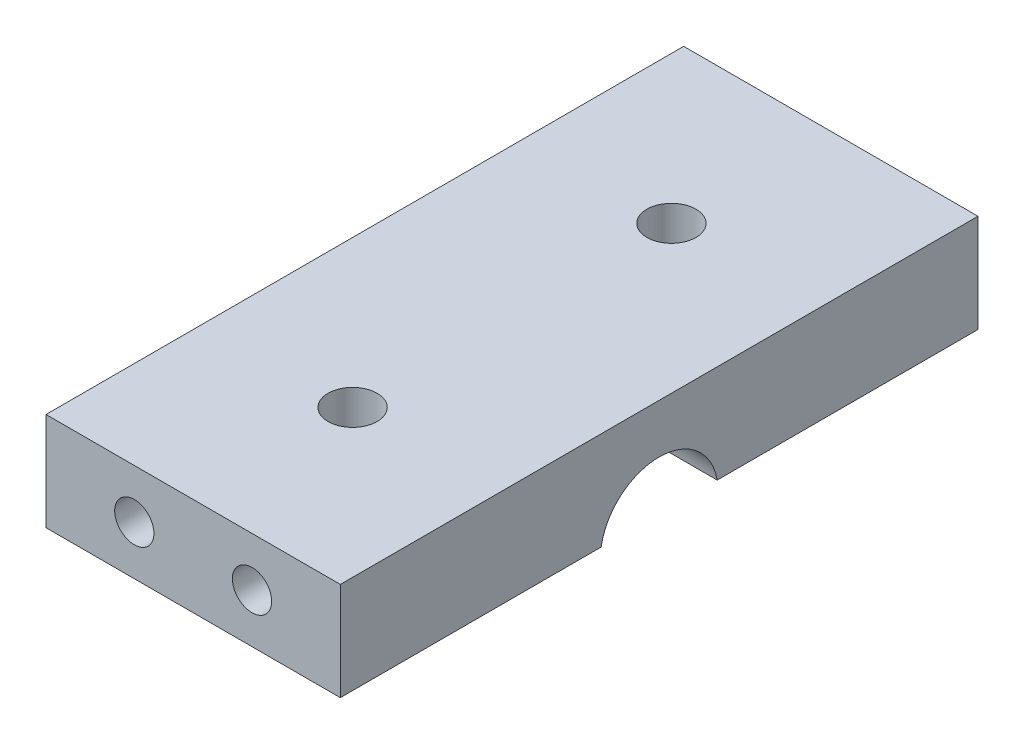
SolidWorks part; units mm, degrees
ref_plane "Спереди" through (0, 0, 0) normal (0, 0, 1) x (1, 0, 0)
ref_plane "Сверху" through (0, 0, 0) normal (0, 1, 0) x (1, 0, 0)
ref_plane "Справа" through (0, 0, 0) normal (1, 0, 0) x (0, 0, -1)
sketch "Эскиз1" plane through (0, 0, 0) normal (0, 1, 0) x (1, 0, 0)
  line L1 (0, 0) -> (30, 0)
  line L2 (0, 0) -> (0, 65)
  line L3 (0, 65) -> (30, 65)
  line L4 (30, 0) -> (30, 65)
extrude "Вытянуть1" add sketch "Эскиз1" along normal blind 10
sketch "Эскиз2" plane through (30, 0, 0) normal (1, 0, 0) x (0, 0, -1)
  line L1 (32.5, 12) -> (32.5, 26.3435) construction
  line L2 (0, 0) -> (65, 0) construction
  line L20 (35.8059, -1) -> (54.9306, -1) construction
  circle A0 centre (32.5, -1) radius 6
  dimension "D1" = 1
extrude "Вытянуть2" cut sketch "Эскиз2" against normal through all
sketch "Эскиз3" plane through (0, 10, 0) normal (0, 1, 0) x (1, 0, 0)
  line L0 (30, 32.5) -> (54.7287, 32.5) construction
  line L3 (38.2078, 16.25) -> (58.5748, 16.25) construction
  line L4 (33.575, 48.75) -> (59.4489, 48.75) construction
  line L5 (15, 65) -> (15, -4.2129) construction
  circle A0 centre (15, 48.75) radius 2.5
  circle A1 centre (15, 16.25) radius 2.5
  dimension "D1" = 16.25
  dimension "D2" = 16.25
extrude "Вытянуть3" cut sketch "Эскиз3" against normal through all
sketch "Эскиз4" plane through (0, 0, 0) normal (0, 0, 1) x (1, 0, 0)
  circle A0 centre (9, 5) radius 2
  circle A1 centre (21, 5) radius 2
extrude "Вырез-Вытянуть1" cut sketch "Эскиз4" against normal blind 20
sketch "Эскиз5" plane through (0, 0, -65) normal (0, 0, -1) x (-1, 0, 0)
  circle A0 centre (-21, 5) radius 2
  circle A1 centre (-9, 5) radius 2
extrude "Вырез-Вытянуть2" cut sketch "Эскиз5" against normal blind 20
